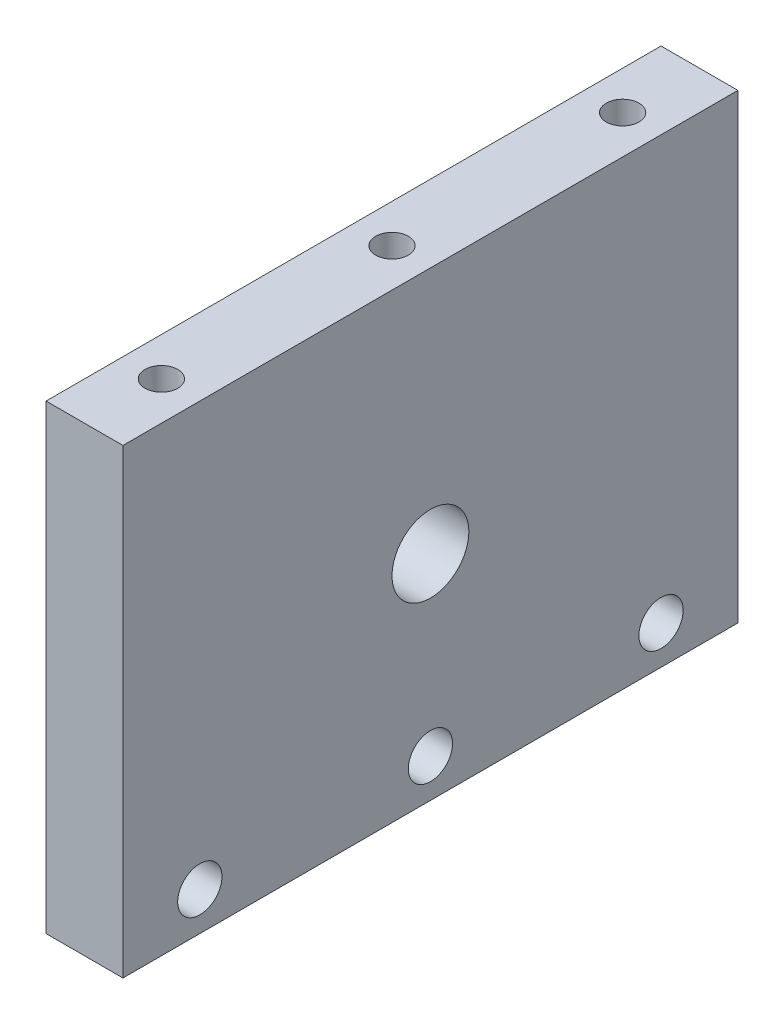
SolidWorks part; units mm, degrees
ref_plane "Front Plane" through (0, 0, 0) normal (0, 0, 1) x (1, 0, 0)
ref_plane "Top Plane" through (0, 0, 0) normal (0, 1, 0) x (1, 0, 0)
ref_plane "Right Plane" through (0, 0, 0) normal (1, 0, 0) x (0, 0, -1)
sketch "Sketch1" plane through (0, 0, 0) normal (1, 0, 0) x (0, 0, -1)
  line L1 (0, 0) -> (-50.8, 0)
  line L2 (0, 0) -> (0, 38.1)
  line L3 (0, 38.1) -> (-50.8, 38.1)
  line L4 (-50.8, 0) -> (-50.8, 38.1)
  dimension "D1" = 38.1
  dimension "D2" = 50.8
extrude "Boss-Extrude1" add sketch "Sketch1" along normal blind 6.35
sketch "Sketch2" plane through (0, 38.1, 0) normal (0, 1, 0) x (1, 0, 0)
  line L0 (0, 0) -> (0, -50.8) construction
  line L1 (6.35, -50.8) -> (0, -50.8) construction
  circle A0 centre (3.175, -44.45) radius 1.7526
  circle A1 centre (3.175, -6.35) radius 1.7526
  circle A3 centre (3.175, -25.4) radius 1.7526
  dimension "D1" = 3.5052
  dimension "D3" = 3.5052
  dimension "D5" = 3.5052
  dimension "D2" = 3.175
  dimension "D4" = 6.35
  dimension "D6" = 25.4
  dimension "D7" = 44.45
sketch "Sketch3" plane through (6.35, 0, 0) normal (1, 0, 0) x (0, 0, -1)
  line L0 (-50.8, 38.1) -> (-50.8, 0) construction
  line L1 (-50.8, 0) -> (0, 0) construction
  circle A0 centre (-44.45, 3.175) radius 1.8288
  circle A1 centre (-25.4, 3.175) radius 1.8288
  circle A2 centre (-6.35, 3.175) radius 1.8288
  dimension "D7" = 3.6576
  dimension "D8" = 3.6576
  dimension "D9" = 3.6576
  dimension "D1" = 6.35
  dimension "D2" = 25.4
  dimension "D3" = 44.45
  dimension "D4" = 3.175
  dimension "D5" = 3.175
  dimension "D6" = 3.175
extrude "Cut-Extrude1" cut sketch "Sketch3" against normal blind 6.35
hole_wizard "#6-32 Tapped Hole1" positions "Sketch10" profile "Sketch11" tap size "#6-32" standard "ANSI Inch"
sketch "Sketch10" plane through (0, 38.1, 0) normal (0, 1, 0) x (1, 0, 0)
  point P0 (3.175, -6.35)
  point P3 (3.175, -25.4)
  point P6 (3.175, -44.45)
sketch "Sketch11" plane through (3.175, 38.1, 6.35) normal (1, 0, 0) x (0, 0, 1)
  line L0 (0, 0) -> (0, 12.7)
  line L1 (0, 12.7) -> (1.3525, 11.8873)
  line L2 (1.3525, 11.8873) -> (1.3525, 0)
  line L5 (1.3525, 0) -> (0, 0)
  line L10 (0, 12.7) -> (-1.3526, 11.8873) construction
  line L11 (0, -6.35) -> (0, 107.95) construction
  dimension "Tap Drill Dia." = 2.7051
  dimension "Tap Drill Depth" = 12.7
  dimension "Drill Angle" = 118
cosmetic thread "Hole Thread1" parameters "D1"=10.16, "D2"=3.5052
cosmetic thread "Hole Thread2" parameters "D1"=10.16, "D2"=3.5052
cosmetic thread "Hole Thread3" parameters "D1"=10.16, "D2"=3.5052
sketch "Sketch12" plane through (6.35, 0, 0) normal (1, 0, 0) x (0, 0, -1)
  line L0 (-50.8, 0) -> (0, 0) construction
  line L1 (-50.8, 38.1) -> (-50.8, 0) construction
  circle A0 centre (-25.4, 17.653) radius 3.175
  dimension "D1" = 6.35
  dimension "D2" = 17.653
  dimension "D3" = 25.4
extrude "Cut-Extrude3" cut sketch "Sketch12" against normal blind 6.35
